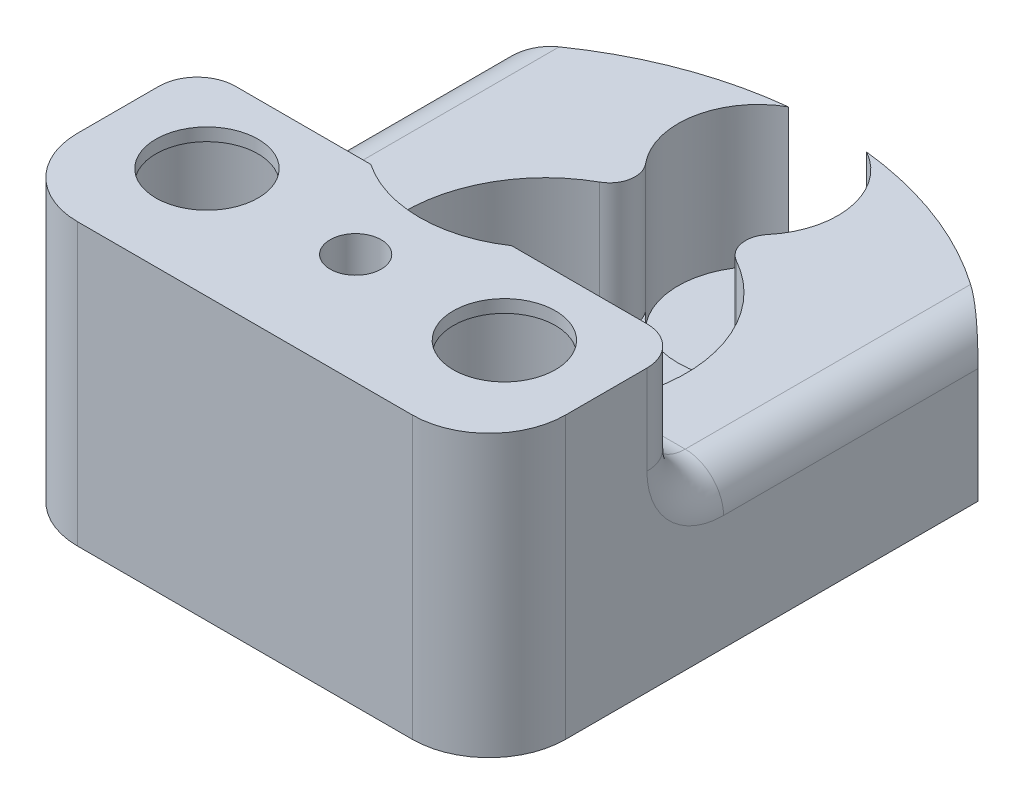
SolidWorks part; units mm, degrees
ref_plane "Front Plane" through (0, 0, 0) normal (0, 0, 1) x (1, 0, 0)
ref_plane "Top Plane" through (0, 0, 0) normal (0, 1, 0) x (1, 0, 0)
ref_plane "Right Plane" through (0, 0, 0) normal (1, 0, 0) x (0, 0, -1)
sketch "Sketch1" plane through (0, 0, 0) normal (0, 1, 0) x (1, 0, 0)
  circle A0 centre (0, 0) radius 34.445
  dimension "D1" = 68.89
extrude "Boss-Extrude1" add sketch "Sketch1" along normal blind 22
sketch "Sketch5" plane through (0, 22, 0) normal (0, 1, 0) x (1, 0, 0)
  line L0 (0, 34.445) -> (0, -34.445) construction
  circle A0 centre (0, 0) radius 34.445 construction
sketch "Sketch15" plane through (0, 22, 0) normal (0, 1, 0) x (1, 0, 0)
  line L1 (-19.1096, 20.6169) -> (-19.1096, -17.6787)
  line L3 (0, 34.445) -> (0, -34.445) construction
  line L4 (-19.1096, -17.6787) -> (19.1096, -17.6787)
  line L5 (0, -17.6787) -> (0, -34.445)
  line L6 (0, 34.445) -> (0, -34.445) construction
  line L7 (19.1096, 20.6169) -> (19.1096, -17.6787)
  arc A1 (-19.1096, 20.6169) -> (19.1096, 20.6169) centre (0, 0) cw
  circle A3 centre (0, 0) radius 34.445
extrude "Cut-Extrude2" cut sketch "Sketch15" against normal through all contours L6 A1 L1 L4 | A1 L6 L4 L7 | A3
sketch "Sketch17" plane through (0, 22, 0) normal (0, 1, 0) x (1, 0, 0)
  line L0 (-19.1096, 1.4691) -> (19.1096, 1.4691) construction
  line L1 (-19.1096, 20.6169) -> (-19.1096, -17.6787) construction
  line L2 (19.1096, 20.6169) -> (19.1096, -17.6787) construction
  line L3 (-11.6441, -9.0085) -> (11.6441, -9.0085)
  circle A0 centre (-11.6441, -9.0085) radius 6.2
  circle A2 centre (11.6441, -9.0085) radius 6.2
extrude "Cut-Extrude4" cut sketch "Sketch17" against normal blind 20 from offset 1 contours A0 | A2 offset against normal yes
sketch "Sketch18" plane through (0, 22, 0) normal (0, 1, 0) x (1, 0, 0)
  line L0 (0, 34.445) -> (0, -34.445) construction
  circle A0 centre (0, 5.8463) radius 7.25
  dimension "D1" = 14.5
extrude "Cut-Extrude5" cut sketch "Sketch18" against normal through all
sketch "Sketch19" plane through (0, 22, 0) normal (0, 1, 0) x (1, 0, 0)
  line L0 (0, 34.445) -> (0, -34.445) construction
  circle A0 centre (0, 22.4979) radius 6.25
  point P4 (0, 21.4967)
  point P5 (0, 20.1303)
  point P6 (0, 22.4979)
  point P9 (0, 28.1111)
  point P10 (0, 0)
  point P11 (0, 0)
  point P12 (0, 21.8611)
  dimension "D1" = 12.5
extrude "Cut-Extrude7" cut sketch "Sketch19" against normal blind 21 contours A0
sketch "Sketch20" plane through (0, 22, 0) normal (0, 1, 0) x (1, 0, 0)
  circle A0 centre (0, 5.8463) radius 9.846
extrude "Cut-Extrude9" cut sketch "Sketch20" against normal blind 10
fillet "Fillet12" radius 6 2 edges at (-19.1096, 11, 17.6787) (19.1096, 11, 17.6787)
sketch "Sketch23" plane through (0, 22, 0) normal (0, 1, 0) x (1, 0, 0)
  line L0 (0, 34.445) -> (0, -34.445) construction
  circle A0 centre (-11.6441, -9.0085) radius 4
  circle A1 centre (11.6441, -9.0085) radius 4
  circle A2 centre (0, -9.0085) radius 2
  dimension "D1" = 2
extrude "Cut-Extrude10" cut sketch "Sketch23" against normal through all
sketch "Sketch24" plane through (0, 0, 0) normal (0, -1, 0) x (1, 0, 0)
  line L0 (19.1096, -20.6169) -> (19.1096, 11.6787) construction
  line L2 (-19.1096, -20.6169) -> (-19.1096, 2.3098)
  line L3 (-19.1096, 2.3098) -> (19.1096, 2.3098)
  line L4 (19.1096, -20.6169) -> (19.1096, 2.3098)
  arc A0 (-19.1096, -20.6169) -> (19.1096, -20.6169) centre (0, 0) ccw
  arc A1 (-19.1096, -20.6169) -> (19.1096, -20.6169) centre (0, 0) ccw construction
extrude "Cut-Extrude11" cut sketch "Sketch24" against normal through all from offset 12 offset against normal yes
fillet "Fillet19" radius 3 6 edges at (-19.1096, 17, 2.3098) (19.1096, 17, 2.3098) (-19.1096, 12, -9.1536) (19.1096, 12, -9.1536) (12.3126, 12, 2.3098) (-12.3126, 12, 2.3098)
sketch "Sketch25" plane through (0, 12, 0) normal (0, 1, 0) x (1, 0, 0)
  circle A0 centre (0, 5.8463) radius 11
  dimension "D1" = 22
extrude "Cut-Extrude12" cut sketch "Sketch25" against normal blind 10
fillet "Fillet20" radius 2 1 edges at (-2.1584, 7, -16.6325)
